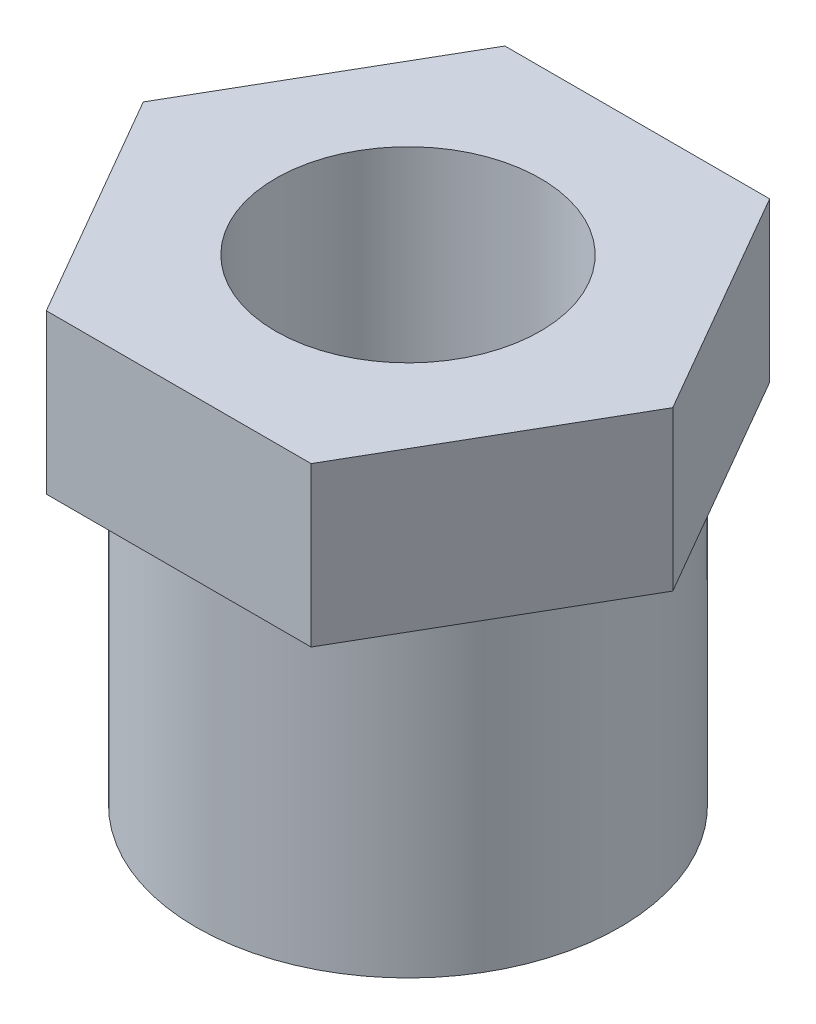
SolidWorks part; units mm, degrees
ref_plane "Front Plane" through (0, 0, 0) normal (0, 0, 1) x (1, 0, 0)
ref_plane "Top Plane" through (0, 0, 0) normal (0, 1, 0) x (1, 0, 0)
ref_plane "Right Plane" through (0, 0, 0) normal (1, 0, 0) x (0, 0, -1)
sketch "Sketch1" plane through (0, 0, 0) normal (0, 1, 0) x (1, 0, 0)
  circle A0 centre (0, 0) radius 4
  dimension "D1" = 8
extrude "Boss-Extrude1" add sketch "Sketch1" along normal blind 6
sketch "Sketch2" plane through (0, 6, 0) normal (0, 1, 0) x (1, 0, 0)
  line L1 (2.5, -4.3301) -> (5, 0)
  line L2 (5, 0) -> (2.5, 4.3301)
  line L3 (2.5, 4.3301) -> (-2.5, 4.3301)
  line L4 (-2.5, 4.3301) -> (-5, 0)
  line L5 (-5, 0) -> (-2.5, -4.3301)
  line L6 (-2.5, -4.3301) -> (2.5, -4.3301)
  circle A0 centre (0, 0) radius 4.3301 construction
  point P1 (0, 0)
  dimension "D1" = 10
extrude "Boss-Extrude2" add sketch "Sketch2" along normal blind 3
sketch "Sketch3" plane through (0, 9, 0) normal (0, 1, 0) x (1, 0, 0)
  circle A0 centre (0, 0) radius 2.5
  dimension "D1" = 5
extrude "Cut-Extrude1" cut sketch "Sketch3" against normal through all
